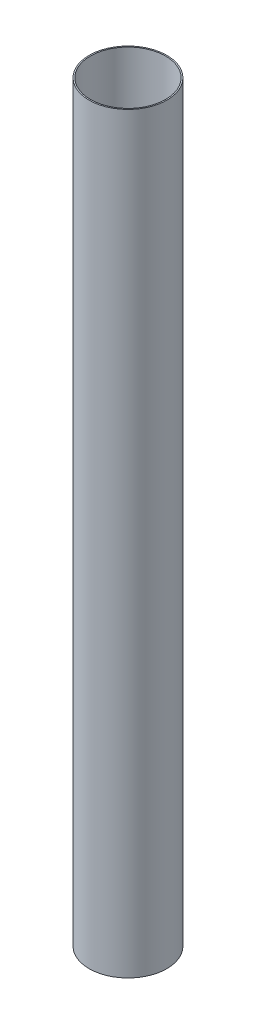
SolidWorks part; units mm, degrees
material "E-Glass Fiber"
ref_plane "Front Plane" through (0, 0, 0) normal (0, 0, 1) x (1, 0, 0)
ref_plane "Top Plane" through (0, 0, 0) normal (0, 1, 0) x (1, 0, 0)
ref_plane "Right Plane" through (0, 0, 0) normal (1, 0, 0) x (0, 0, -1)
sketch "Sketch1" plane through (0, 0, 0) normal (0, 1, 0) x (1, 0, 0)
  circle A0 centre (0, 0) radius 39.37
  circle A1 centre (0, 0) radius 38.1
  dimension "D1" = 78.74
  dimension "D2" = 76.2
extrude "Boss-Extrude2" add sketch "Sketch1" along normal blind 762
